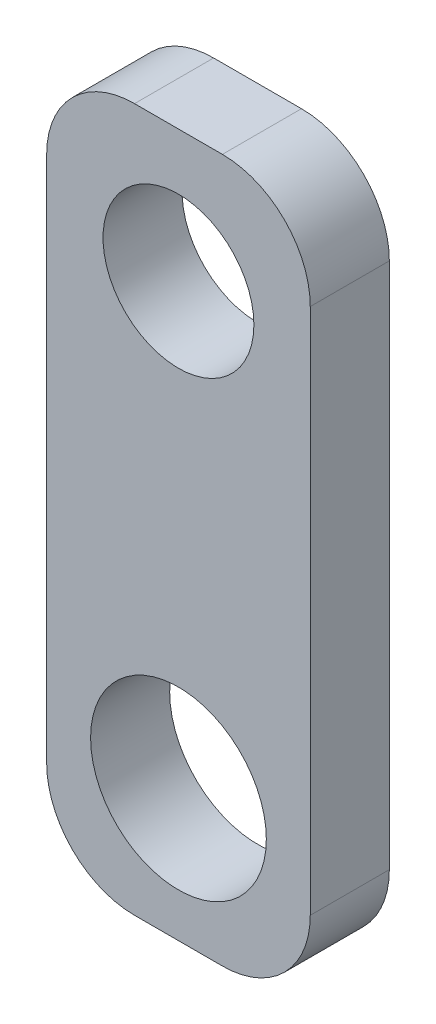
SolidWorks part; units mm, degrees
material "A36 Steel"
ref_plane "Front Plane" through (0, 0, 0) normal (0, 0, 1) x (1, 0, 0)
ref_plane "Top Plane" through (0, 0, 0) normal (0, 1, 0) x (1, 0, 0)
ref_plane "Right Plane" through (0, 0, 0) normal (1, 0, 0) x (0, 0, -1)
sketch "Sketch1" plane through (0, 0, 0) normal (0, 0, 1) x (1, 0, 0)
  line L1 (12.7, 0) -> (25.4, 0)
  line L2 (0, 12.7) -> (0, 88.9)
  line L3 (12.7, 101.6) -> (25.4, 101.6)
  line L4 (38.1, 12.7) -> (38.1, 88.9)
  line L5 (0, 50.8) -> (38.1, 50.8) construction
  line L6 (19.05, 19.05) -> (19.05, 82.55) construction
  circle A1 centre (19.05, 82.55) radius 10.903
  circle A2 centre (19.05, 19.05) radius 12.7
  arc A3 (12.7, 0) -> (0, 12.7) centre (12.7, 12.7) cw
  arc A4 (25.4, 0) -> (38.1, 12.7) centre (25.4, 12.7) ccw
  arc A5 (25.4, 101.6) -> (38.1, 88.9) centre (25.4, 88.9) cw
  arc A6 (0, 88.9) -> (12.7, 101.6) centre (12.7, 88.9) cw
  point P13 (19.05, 50.8)
  point P15 (0, 0)
  point P18 (38.1, 0)
  point P21 (38.1, 101.6)
  point P24 (0, 101.6)
  dimension "D1" = 21.8059
  dimension "D2" = 25.4
  dimension "D6" = 12.7
  dimension "D4" = 101.6
  dimension "D5" = 38.1
  dimension "D3" = 63.5
extrude "Boss-Extrude1" add sketch "Sketch1" along normal blind 11.43
ref_plane "Plane1" through (0, 31.75, 0) normal (0, -1, 0) x (-1, 0, 0)
equation "\"Hole_A\"= 0.8585"
equation "\"Hole_B\"= 1.0"
equation "\"L\"= 4'T"
equation "\"T\"= .25"
equation "\"W\"= 1.5"
equation "\"D4@Sketch1\"=\"L\""
equation "\"Hole_Spacing\"= 2.5"
equation "\"D3@Sketch1\"=\"Hole_Spacing\""
equation "\"D2@Sketch1\"=\"Hole_B\""
equation "\"D1@Sketch1\"=\"Hole_A\""
equation "\"D5@Sketch1\"=\"W\""
equation "\"D1@Boss-Extrude1\"=\"T\""
